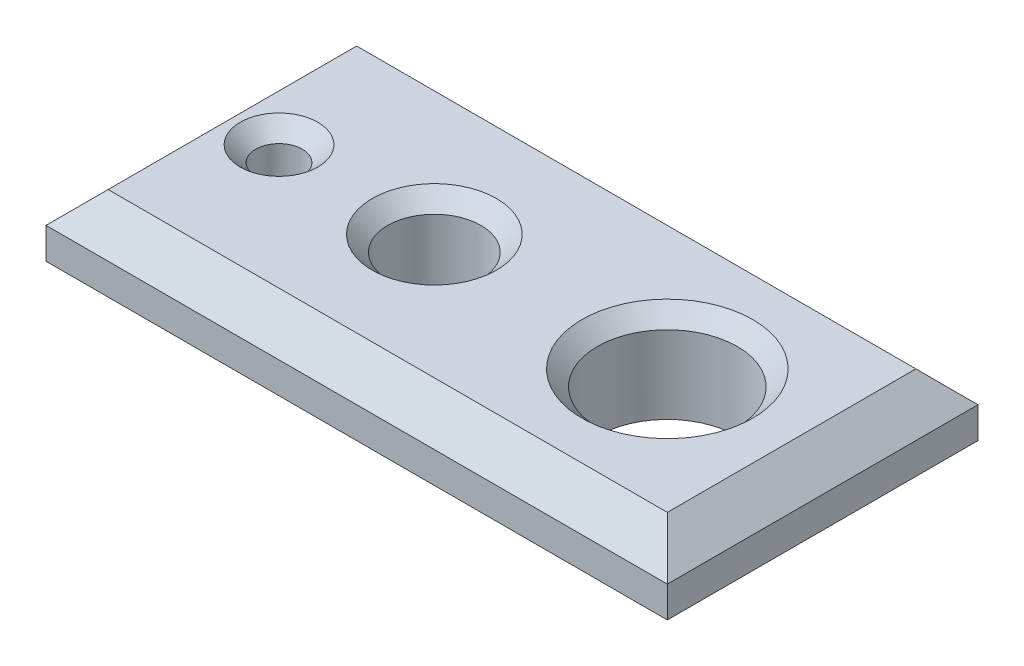
SolidWorks part; units mm, degrees
ref_plane "前基準面" through (0, 0, 0) normal (0, 0, 1) x (1, 0, 0)
ref_plane "上基準面" through (0, 0, 0) normal (0, 1, 0) x (1, 0, 0)
ref_plane "右基準面" through (0, 0, 0) normal (1, 0, 0) x (0, 0, -1)
sketch "草圖1" plane through (0, 0, 0) normal (0, 1, 0) x (1, 0, 0)
  line L1 (0, 0) -> (200, 0)
  line L2 (0, 0) -> (0, 100)
  line L3 (0, 100) -> (200, 100)
  line L4 (200, 0) -> (200, 100)
  dimension "D1" = 100
  dimension "D2" = 200
extrude "填料-伸長1" add sketch "草圖1" along normal blind 30
sketch "草圖2" plane through (0, 30, 0) normal (0, 1, 0) x (1, 0, 0)
  line L0 (25, 50) -> (75, 50)
  line L1 (75, 50) -> (150, 50)
  line L2 (0, 50) -> (25, 50)
  line L3 (0, 100) -> (0, 0) construction
  circle A0 centre (25, 50) radius 7.5
  circle A1 centre (75, 50) radius 15
  circle A2 centre (150, 50) radius 22.5
  dimension "D4" = 30
  dimension "D5" = 45
  dimension "D6" = 15
  dimension "D1" = 25
  dimension "D2" = 50
  dimension "D3" = 75
extrude "除料-伸長1" cut sketch "草圖2" against normal blind 30
chamfer "導角1" distance 10 angle 45 8 edges at (100, 0, 0) (200, 0, -50) (100, 0, -100) (0, 0, -50) (200, 30, -50) (100, 30, 0) (100, 30, -100) (0, 30, -50)
chamfer "導角3" distance 5 angle 45 3 edges at (150, 30, -27.5) (75, 30, -35) (25, 30, -42.5)
